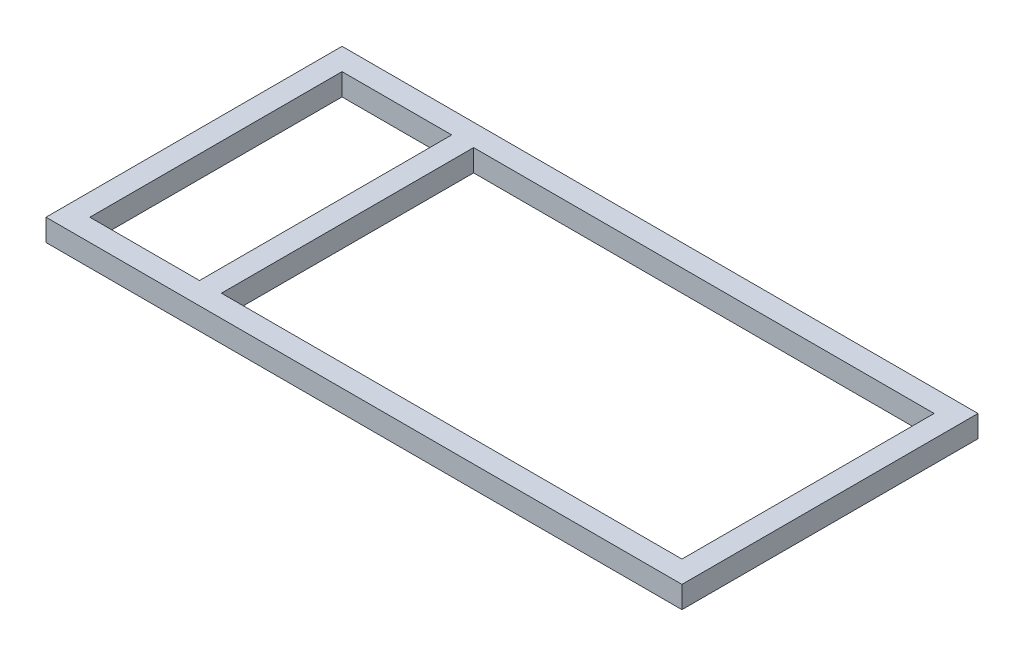
SolidWorks part; units mm, degrees
ref_plane "Front Plane" through (0, 0, 0) normal (0, 0, 1) x (1, 0, 0)
ref_plane "Top Plane" through (0, 0, 0) normal (0, 1, 0) x (1, 0, 0)
ref_plane "Right Plane" through (0, 0, 0) normal (1, 0, 0) x (0, 0, -1)
sketch "Sketch1" plane through (0, 0, 0) normal (0, 1, 0) x (1, 0, 0)
  line L0 (152.4, 317.5) -> (152.4, 25.4)
  line L1 (0, 0) -> (736.6, 0)
  line L2 (0, 0) -> (0, 342.9)
  line L3 (0, 342.9) -> (736.6, 342.9)
  line L4 (736.6, 0) -> (736.6, 342.9)
  line L5 (25.4, 25.4) -> (152.4, 25.4)
  line L6 (25.4, 25.4) -> (25.4, 317.5)
  line L7 (25.4, 317.5) -> (152.4, 317.5)
  line L8 (711.2, 25.4) -> (711.2, 317.5)
  line L10 (177.8, 25.4) -> (177.8, 317.5)
  line L11 (177.8, 317.5) -> (711.2, 317.5)
  line L12 (177.8, 25.4) -> (711.2, 25.4)
  dimension "D1" = 736.6
  dimension "D2" = 342.9
  dimension "D3" = 25.4
  dimension "D4" = 25.4
  dimension "D5" = 25.4
  dimension "D6" = 292.1
  dimension "D7" = 25.4
  dimension "D8" = 127
extrude "Boss-Extrude1" add sketch "Sketch1" along normal blind 25.4
